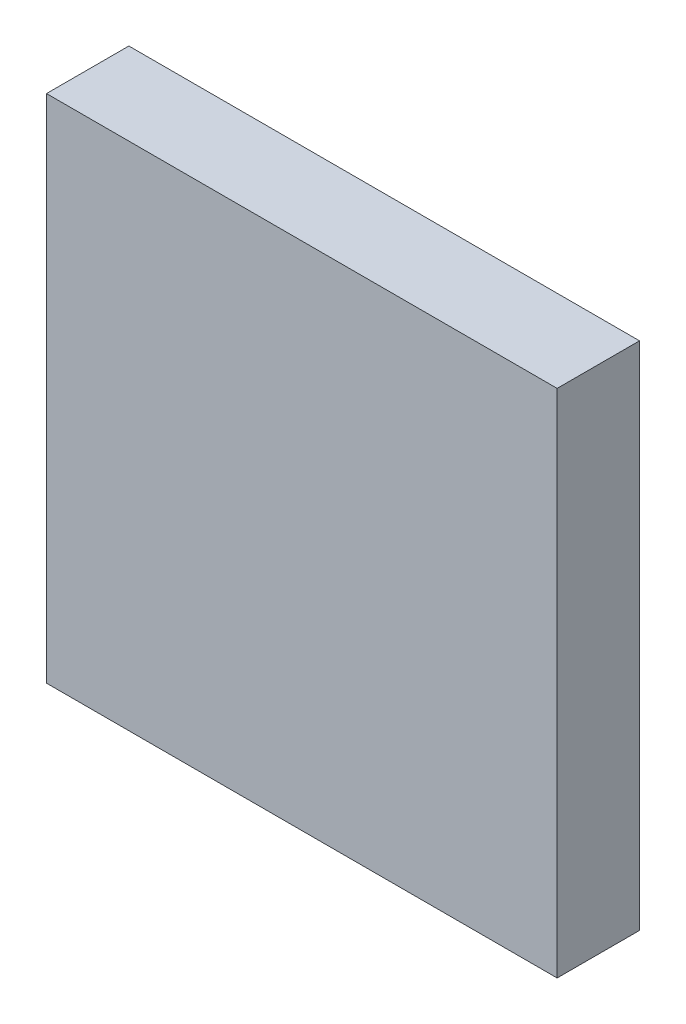
SolidWorks part; units mm, degrees
ref_plane "Спереди" through (0, 0, 0) normal (0, 0, 1) x (1, 0, 0)
ref_plane "Сверху" through (0, 0, 0) normal (0, 1, 0) x (1, 0, 0)
ref_plane "Справа" through (0, 0, 0) normal (1, 0, 0) x (0, 0, -1)
sketch "Эскиз5" plane through (0, 0, 0) normal (0, 0, 1) x (1, 0, 0)
  line L1 (-31, -31) -> (31, -31)
  line L2 (-31, -31) -> (-31, 31)
  line L3 (-31, 31) -> (31, 31)
  line L4 (31, -31) -> (31, 31)
  line L5 (-31, -31) -> (31, 31) construction
  line L6 (-31, 31) -> (31, -31) construction
  point P0 (0, 0)
extrude "Бобышка-Вытянуть2" add sketch "Эскиз5" along normal blind 10 contours L2 L3 L4 L1
sketch "Эскиз13" plane through (0, 0, 10) normal (0, 0, 1) x (1, 0, 0)
  line L1 (8.5, 3.8388) -> (8.5, -2.9703)
  line L2 (-8.5, -2.9278) -> (-8.5, 3.8388)
  spline S0 degree 3 poles (3.7602, -6.2881) (4.1456, -5.7125) (4.7609, -5.3316) (5.448, -5.2431) knots 0 0 0 0 0.333333 0.333333 0.333333 0.333333
  spline S1 degree 3 poles (5.448, -5.2431) (6.135, -5.1547) (6.8268, -5.3675) (7.3454, -5.8267) knots 0.333333 0.333333 0.333333 0.333333 1 1 1 1
  spline S2 degree 3 poles (8.2703, 4.2595) (8.4134, 4.1675) (8.5, 4.009) (8.5, 3.8388) knots 0 0 0 0 1 1 1 1
  spline S3 degree 3 poles (-8.2703, 4.2595) (-3.2319, 7.4966) (3.2319, 7.4966) (8.2703, 4.2595) knots 0 0 0 0 1 1 1 1
  spline S4 degree 3 poles (-8.5, 3.8388) (-8.5, 4.009) (-8.4134, 4.1675) (-8.2703, 4.2595) knots 0 0 0 0 1 1 1 1
  spline S5 degree 3 poles (8.9672, -4.0581) (8.6689, -3.7749) (8.5, -3.3816) (8.5, -2.9703) knots 0 0 0 0 1 1 1 1
  spline S6 degree 3 poles (8.9672, -4.0581) (9.4419, -4.5088) (9.4678, -5.2568) (9.0253, -5.7393) knots 0 0 0 0 0.333333 0.333333 0.333333 0.333333
  spline S7 degree 3 poles (9.0253, -5.7393) (8.5829, -6.2218) (7.8355, -6.2607) (7.3454, -5.8267) knots 0.333333 0.333333 0.333333 0.333333 1 1 1 1
  spline S8 degree 3 poles (-8.5, -2.9278) (-8.5, -3.3579) (-8.6732, -3.77) (-8.9805, -4.0709) knots 0 0 0 0 1 1 1 1
  spline S9 degree 3 poles (-7.6987, -6.0438) (-6.4648, -5.5547) (-5.0779, -5.6352) (-3.9089, -6.2639) knots 0 0 0 0 1 1 1 1
  spline S10 degree 3 poles (-7.6987, -6.0438) (-8.2299, -6.2544) (-8.8358, -6.0612) (-9.1472, -5.5821) knots 0 0 0 0 0.333333 0.333333 0.333333 0.333333
  spline S11 degree 3 poles (-9.1472, -5.5821) (-9.4585, -5.1029) (-9.3888, -4.4707) (-8.9805, -4.0709) knots 0.333333 0.333333 0.333333 0.333333 1 1 1 1
  spline S12 degree 3 poles (-3.1792, -6.3186) (-1.2825, -5.6394) (0.8063, -5.741) (2.6281, -6.6012) knots 0 0 0 0 1 1 1 1
  spline S13 degree 3 poles (3.7602, -6.2881) (3.5123, -6.6582) (3.0309, -6.7914) (2.6281, -6.6012) knots 0 0 0 0 1 1 1 1
  spline S14 degree 3 poles (-3.1792, -6.3186) (-3.4192, -6.4045) (-3.6844, -6.3847) (-3.9089, -6.2639) knots 0 0 0 0 1 1 1 1
sketch "остров" plane through (0, 0, 10) normal (0, 0, 1) x (1, 0, 0)
  spline S40 degree 3 poles (-5.7898, -5.6368) (-5.8728, -5.6949) (-5.9715, -5.7264) (-6.0728, -5.7271) knots 0 0 0 0 1 1 1 1
  spline S41 degree 3 poles (5.4083, -5.2485) (5.2964, -5.2648) (5.1822, -5.2427) (5.0845, -5.1857) knots 0 0 0 0 1 1 1 1
  spline S42 degree 3 poles (3.7602, -6.288) (4.1382, -5.7235) (4.7372, -5.3463) (5.4083, -5.2484) knots 0 0 0 0 0.3269 0.3269 0.3269 0.3269
  spline S47 degree 3 poles (-5.7898, -5.6368) (-2.563, -3.3793) (1.6818, -3.2032) (5.0845, -5.1857) knots 0 0 0 0 1 1 1 1
  spline S52 degree 3 poles (-6.0728, -5.7271) (-5.3265, -5.7218) (-4.5816, -5.902) (-3.9089, -6.2638) knots 0.424548 0.424548 0.424548 0.424548 1 1 1 1
  spline S55 degree 3 poles (-3.1792, -6.3185) (-1.2825, -5.6393) (0.8063, -5.7409) (2.6281, -6.6011) knots 0 0 0 0 1 1 1 1
  spline S56 degree 3 poles (3.7602, -6.288) (3.5123, -6.6581) (3.0309, -6.7913) (2.6281, -6.6011) knots 0 0 0 0 1 1 1 1
  spline S57 degree 3 poles (-3.1792, -6.3185) (-3.4192, -6.4044) (-3.6844, -6.3846) (-3.9089, -6.2638) knots 0 0 0 0 1 1 1 1
sketch "карман под съем моста" plane through (0, 0, 10) normal (0, 0, 1) x (1, 0, 0)
  line L0 (-13.7619, 0) -> (13.4181, 0) construction
  line L1 (-13.7619, 1) -> (13.4181, 1)
  line L2 (-13.7619, -1) -> (13.4181, -1)
  arc A0 (-13.7619, 1) -> (-13.7619, -1) centre (-13.7619, 0) ccw
  arc A1 (13.4181, -1) -> (13.4181, 1) centre (13.4181, 0) ccw
  point P3 (-0.1719, 0)
sketch "уголки" plane through (0, 0, 10) normal (0, 0, 1) x (1, 0, 0)
  spline S0 degree 2 poles (8.5, -2.0317) (8.5, -2.5998) (8.5, -2.9703) knots 0 0 0 1 1 1
  spline S1 degree 3 poles (5.4691, 5.3435) (5.4628, 5.5492) (5.3311, 5.73) (5.1372, 5.7991) knots 0 0 0 0 1 1 1 1
  spline S2 degree 3 poles (8.3317, 4.2129) (8.1698, 4.2866) (7.9808, 4.2686) (7.8357, 4.1657) knots 0 0 0 0 1 1 1 1
  spline S3 degree 3 poles (8.3317, 4.2129) (8.3126, 4.2298) (8.2921, 4.2455) (8.2703, 4.2595) knots 0 0 0 0 1 1 1 1
  spline S4 degree 3 poles (8.0243, -2.5311) (8.2907, -2.5182) (8.5, -2.2984) (8.5, -2.0317) knots 0 0 0 0 1 1 1 1
  spline S5 degree 3 poles (8.0243, -2.5311) (6.7965, -2.5908) (5.8123, -3.5687) (5.7445, -4.7961) knots 0 0 0 0 1 1 1 1
  spline S6 degree 3 poles (5.3331, -5.2608) (5.5614, -5.2201) (5.7318, -5.0277) (5.7445, -4.7961) knots 0 0 0 0 1 1 1 1
  spline S7 degree 3 poles (-6.4277, -5.7438) (-6.8591, -5.781) (-7.2875, -5.8808) (-7.6987, -6.0438) knots 0 0 0 0 1 1 1 1
  spline S8 degree 3 poles (-6.962, -5.1523) (-6.9912, -5.3061) (-6.9468, -5.4647) (-6.8418, -5.5808) knots 0 0 0 0 0.333333 0.333333 0.333333 0.333333
  spline S9 degree 3 poles (-6.8418, -5.5808) (-6.7369, -5.697) (-6.5837, -5.7573) (-6.4277, -5.7438) knots 0.333333 0.333333 0.333333 0.333333 1 1 1 1
  spline S10 degree 3 poles (-6.962, -5.1523) (-6.898, -4.8155) (-6.9811, -4.4674) (-7.1904, -4.1958) knots 0 0 0 0 0.333333 0.333333 0.333333 0.333333
  spline S11 degree 3 poles (-7.1904, -4.1958) (-7.3997, -3.9242) (-7.7151, -3.7551) (-8.0571, -3.7312) knots 0.333333 0.333333 0.333333 0.333333 1 1 1 1
  spline S12 degree 3 poles (-8.5169, -3.1599) (-8.5371, -3.2976) (-8.499, -3.4375) (-8.4117, -3.5459) knots 0 0 0 0 0.333333 0.333333 0.333333 0.333333
  spline S13 degree 3 poles (-8.4117, -3.5459) (-8.3245, -3.6543) (-8.196, -3.7215) (-8.0571, -3.7312) knots 0.333333 0.333333 0.333333 0.333333 1 1 1 1
  spline S14 degree 3 poles (-8.9805, -4.0709) (-8.729, -3.8247) (-8.5673, -3.504) (-8.5169, -3.1599) knots 0 0 0 0 1 1 1 1
  spline S15 degree 3 poles (-8.2703, 4.2595) (-8.2921, 4.2455) (-8.3126, 4.2298) (-8.3317, 4.2129) knots 0 0 0 0 1 1 1 1
  spline S16 degree 3 poles (-7.8357, 4.1657) (-7.9808, 4.2686) (-8.1698, 4.2866) (-8.3317, 4.2129) knots 0 0 0 0 1 1 1 1
  spline S17 degree 3 poles (-7.8357, 4.1657) (-7.3848, 3.8462) (-6.7948, 3.8005) (-6.3001, 4.0467) knots 0 0 0 0 0.333333 0.333333 0.333333 0.333333
  spline S18 degree 3 poles (-6.3001, 4.0467) (-5.8054, 4.2929) (-5.4861, 4.7912) (-5.4691, 5.3435) knots 0.333333 0.333333 0.333333 0.333333 1 1 1 1
  spline S19 degree 3 poles (-5.1372, 5.7991) (-5.3311, 5.73) (-5.4628, 5.5492) (-5.4691, 5.3435) knots 0 0 0 0 1 1 1 1
  spline S20 degree 3 poles (8.2703, 4.2595) (7.2743, 4.8994) (6.2227, 5.4129) (5.1372, 5.7991) knots 0 0 0 0 1 1 1 1
  spline S21 degree 3 poles (-5.1372, 5.7991) (-6.2227, 5.4129) (-7.2744, 4.8994) (-8.2703, 4.2595) knots 0 0 0 0 1 1 1 1
  spline S22 degree 3 poles (7.3454, -5.8267) (6.8268, -5.3675) (6.135, -5.1547) (5.448, -5.2431) knots 0 0 0 0 0.333333 0.333333 0.333333 0.333333
  spline S23 degree 3 poles (5.448, -5.2431) (5.4095, -5.2481) (5.3711, -5.254) (5.3331, -5.2608) knots 0.333333 0.333333 0.333333 0.333333 1 1 1 1
  spline S24 degree 3 poles (5.4691, 5.3435) (5.4861, 4.7912) (5.8054, 4.2929) (6.3001, 4.0467) knots 0 0 0 0 0.333333 0.333333 0.333333 0.333333
  spline S25 degree 3 poles (6.3001, 4.0467) (6.7948, 3.8005) (7.3848, 3.8462) (7.8357, 4.1657) knots 0.333333 0.333333 0.333333 0.333333 1 1 1 1
  spline S26 degree 3 poles (8.5, -2.9703) (8.5, -3.3816) (8.6689, -3.7749) (8.9672, -4.0581) knots 0 0 0 0 1 1 1 1
  spline S27 degree 3 poles (-8.9805, -4.0709) (-9.3888, -4.4707) (-9.4585, -5.1029) (-9.1472, -5.5821) knots 0 0 0 0 0.333333 0.333333 0.333333 0.333333
  spline S28 degree 3 poles (-9.1472, -5.5821) (-8.8358, -6.0612) (-8.2299, -6.2544) (-7.6987, -6.0438) knots 0.333333 0.333333 0.333333 0.333333 1 1 1 1
  spline S29 degree 3 poles (7.3454, -5.8267) (7.8355, -6.2607) (8.5829, -6.2218) (9.0253, -5.7393) knots 0 0 0 0 0.333333 0.333333 0.333333 0.333333
  spline S30 degree 3 poles (9.0253, -5.7393) (9.4678, -5.2568) (9.4419, -4.5088) (8.9672, -4.0581) knots 0.333333 0.333333 0.333333 0.333333 1 1 1 1
sketch "перлаж задник" plane through (0, 0, 10) normal (0, 0, 1) x (1, 0, 0)
  circle A0 centre (-4.6511, 5.6454) radius 1
  circle A1 centre (-3.4824, 5.7785) radius 1
  circle A2 centre (-2.3098, 5.8733) radius 1
  circle A3 centre (-1.1349, 5.9297) radius 1
  circle A4 centre (0.0413, 5.9476) radius 1
  circle A5 centre (1.2175, 5.927) radius 1
  circle A6 centre (2.3923, 5.8679) radius 1
  circle A7 centre (3.5646, 5.7704) radius 1
  circle A8 centre (4.7331, 5.6346) radius 1
  circle A9 centre (-5.0179, 4.5886) radius 1
  circle A10 centre (-3.7554, 4.7417) radius 1
  circle A11 centre (-2.4883, 4.8507) radius 1
  circle A12 centre (-1.2181, 4.9154) radius 1
  circle A13 centre (0.0535, 4.9357) radius 1
  circle A14 centre (1.3251, 4.9116) radius 1
  circle A15 centre (2.595, 4.8432) radius 1
  circle A16 centre (3.8618, 4.7305) radius 1
  circle A17 centre (5.1239, 4.5737) radius 1
  circle A18 centre (-8.123, 3.2151) radius 1
  circle A19 centre (-7.0541, 3.4447) radius 1
  circle A20 centre (-5.9787, 3.6418) radius 1
  circle A21 centre (-4.8979, 3.8064) radius 1
  circle A22 centre (-3.8126, 3.9381) radius 1
  circle A23 centre (-2.7238, 4.037) radius 1
  circle A24 centre (-1.6325, 4.1029) radius 1
  circle A25 centre (-0.5398, 4.1358) radius 1
  circle A26 centre (0.5535, 4.1356) radius 1
  circle A27 centre (1.6463, 4.1023) radius 1
  circle A28 centre (2.7375, 4.036) radius 1
  circle A29 centre (3.8263, 3.9367) radius 1
  circle A30 centre (4.9116, 3.8045) radius 1
  circle A31 centre (5.9923, 3.6396) radius 1
  circle A32 centre (7.0676, 3.442) radius 1
  circle A33 centre (8.1364, 3.212) radius 1
  circle A34 centre (-8.1008, 2.0704) radius 1
  circle A35 centre (-6.96, 2.3145) radius 1
  circle A36 centre (-5.8119, 2.5215) radius 1
  circle A37 centre (-4.6577, 2.6912) radius 1
  circle A38 centre (-3.4986, 2.8234) radius 1
  circle A39 centre (-2.3358, 2.9179) radius 1
  circle A40 centre (-1.1706, 2.9748) radius 1
  circle A41 centre (-0.0041, 2.9938) radius 1
  circle A42 centre (1.1624, 2.975) radius 1
  circle A43 centre (2.3276, 2.9185) radius 1
  circle A44 centre (3.4904, 2.8242) radius 1
  circle A45 centre (4.6496, 2.6922) radius 1
  circle A46 centre (5.8038, 2.5228) radius 1
  circle A47 centre (6.952, 2.3161) radius 1
  circle A48 centre (8.0929, 2.0722) radius 1
  circle A49 centre (-8.0193, 0.9076) radius 1
  circle A50 centre (-6.8839, 1.1491) radius 1
  circle A51 centre (-5.7411, 1.3538) radius 1
  circle A52 centre (-4.5924, 1.5213) radius 1
  circle A53 centre (-3.4388, 1.6514) radius 1
  circle A54 centre (-2.2816, 1.7441) radius 1
  circle A55 centre (-1.1221, 1.7993) radius 1
  circle A56 centre (0.0387, 1.8169) radius 1
  circle A57 centre (1.1994, 1.7968) radius 1
  circle A58 centre (2.3589, 1.7391) radius 1
  circle A59 centre (3.5158, 1.6439) radius 1
  circle A60 centre (4.6691, 1.5112) radius 1
  circle A61 centre (5.8175, 1.3413) radius 1
  circle A62 centre (6.9598, 1.1342) radius 1
  circle A63 centre (8.0947, 0.8902) radius 1
  circle A64 centre (-7.9633, -0.2579) radius 1
  circle A65 centre (-6.8332, -0.0181) radius 1
  circle A66 centre (-5.6959, 0.185) radius 1
  circle A67 centre (-4.5527, 0.3511) radius 1
  circle A68 centre (-3.4046, 0.4801) radius 1
  circle A69 centre (-2.253, 0.5718) radius 1
  circle A70 centre (-1.099, 0.6261) radius 1
  circle A71 centre (0.0561, 0.643) radius 1
  circle A72 centre (1.2112, 0.6225) radius 1
  circle A73 centre (2.365, 0.5645) radius 1
  circle A74 centre (3.5163, 0.4692) radius 1
  circle A75 centre (4.6639, 0.3366) radius 1
  circle A76 centre (5.8066, 0.1669) radius 1
  circle A77 centre (6.9433, -0.0397) radius 1
  circle A78 centre (8.0726, -0.2831) radius 1
  circle A79 centre (-7.9918, -1.4333) radius 1
  circle A80 centre (-6.8673, -1.1924) radius 1
  circle A81 centre (-5.7357, -0.9882) radius 1
  circle A82 centre (-4.598, -0.8207) radius 1
  circle A83 centre (-3.4555, -0.6901) radius 1
  circle A84 centre (-2.3094, -0.5967) radius 1
  circle A85 centre (-1.1609, -0.5405) radius 1
  circle A86 centre (-0.0111, -0.5215) radius 1
  circle A87 centre (1.1387, -0.5397) radius 1
  circle A88 centre (2.2873, -0.5953) radius 1
  circle A89 centre (3.4334, -0.688) radius 1
  circle A90 centre (4.576, -0.8178) radius 1
  circle A91 centre (5.7138, -0.9846) radius 1
  circle A92 centre (6.8455, -1.1881) radius 1
  circle A93 centre (7.9701, -1.4283) radius 1
  circle A94 centre (-8.0131, -2.6484) radius 1
  circle A95 centre (-6.9172, -2.4111) radius 1
  circle A96 centre (-5.8144, -2.2087) radius 1
  circle A97 centre (-4.7056, -2.0415) radius 1
  circle A98 centre (-3.5921, -1.9096) radius 1
  circle A99 centre (-2.4749, -1.8131) radius 1
  circle A100 centre (-1.3553, -1.7522) radius 1
  circle A101 centre (-0.2343, -1.727) radius 1
  circle A102 centre (0.887, -1.7374) radius 1
  circle A103 centre (2.0074, -1.7834) radius 1
  circle A104 centre (3.1257, -1.865) radius 1
  circle A105 centre (4.2409, -1.9821) radius 1
  circle A106 centre (5.3517, -2.1346) radius 1
  circle A107 centre (6.4572, -2.3223) radius 1
  circle A108 centre (7.5562, -2.545) radius 1
  circle A109 centre (-7.0918, -3.6392) radius 1
  circle A110 centre (-5.9238, -3.4052) radius 1
  circle A111 centre (-4.7481, -3.2133) radius 1
  circle A112 centre (-3.5663, -3.0638) radius 1
  circle A113 centre (-2.3798, -2.9568) radius 1
  circle A114 centre (-1.1903, -2.8926) radius 1
  circle A115 centre (0.0008, -2.8713) radius 1
  circle A116 centre (1.1919, -2.8927) radius 1
  circle A117 centre (2.3814, -2.957) radius 1
  circle A118 centre (3.5678, -3.0639) radius 1
  circle A119 centre (4.7497, -3.2135) radius 1
  circle A120 centre (5.9253, -3.4055) radius 1
  circle A121 centre (-6.2553, -4.6679) radius 1
  circle A122 centre (-5.1231, -4.4693) radius 1
  circle A123 centre (-3.9847, -4.3103) radius 1
  circle A124 centre (-2.8414, -4.1912) radius 1
  circle A125 centre (-1.6947, -4.112) radius 1
  circle A126 centre (-0.5458, -4.0729) radius 1
  circle A127 centre (0.6036, -4.0739) radius 1
  circle A128 centre (1.7524, -4.115) radius 1
  circle A129 centre (2.899, -4.1962) radius 1
  circle A130 centre (4.042, -4.3173) radius 1
  circle A131 centre (5.1802, -4.4783) radius 1
  circle A132 centre (-5.6707, -5.6462) radius 1
  circle A133 centre (-4.4381, -5.46) radius 1
  circle A134 centre (-3.1996, -5.3193) radius 1
  circle A135 centre (-1.9567, -5.2243) radius 1
  circle A136 centre (-0.7112, -5.1751) radius 1
  circle A137 centre (0.5353, -5.1719) radius 1
  circle A138 centre (1.7811, -5.2145) radius 1
  circle A139 centre (3.0245, -5.3031) radius 1
  circle A140 centre (4.2637, -5.4374) radius 1
  circle A141 centre (5.4972, -5.6172) radius 1
  circle A142 centre (-4.869, -6.5621) radius 1
  circle A143 centre (-3.7069, -6.4218) radius 1
  circle A144 centre (-2.5409, -6.3195) radius 1
  circle A145 centre (-1.3721, -6.2555) radius 1
  circle A146 centre (-0.2018, -6.2298) radius 1
  circle A147 centre (0.9687, -6.2423) radius 1
  circle A148 centre (2.1381, -6.2931) radius 1
  circle A149 centre (3.3053, -6.3822) radius 1
  circle A150 centre (4.4689, -6.5094) radius 1
  point P24 (0, -30)
  point P43 (0, -31.5)
  point P76 (0, -32)
  point P107 (0, -33)
  point P138 (0, -34)
  point P169 (0, -35)
  point P200 (0, -36)
  point P231 (0, -37)
  point P256 (0, -36)
  point P279 (0, -37)
  point P300 (0, -39)
  point P319 (0, -42)
  dimension "D1" = 9
  dimension "D2" = 9
  dimension "D3" = 16
  dimension "D4" = 15
  dimension "D5" = 15
  dimension "D6" = 15
  dimension "D7" = 15
  dimension "D8" = 15
  dimension "D9" = 12
  dimension "D10" = 11
  dimension "D11" = 10
  dimension "D12" = 9
sketch "подточка" plane through (0, 0, 10) normal (0, 0, 1) x (1, 0, 0)
  circle A0 centre (-8.7716, 9.2306) radius 1
  circle A1 centre (-5.299, 10.4616) radius 1
  circle A2 centre (-1.6654, 11.0709) radius 1
  circle A3 centre (2.0189, 11.04) radius 1
  circle A4 centre (5.6417, 10.3697) radius 1
  circle A5 centre (9.0932, 9.0806) radius 1
  point P15 (0, -10)
  dimension "D1" = 6
sketch "Перлаж сетка"
  point P35 (0, -9)
  point P68 (0, -10)
  dimension "D1" = 11
sketch_block_instance "Блок4-18"
sketch_block "Блок4"
sketch_block_instance "Блок4-19"
sketch_block_instance "Блок4-20"
sketch_block_instance "Блок4-21"
sketch_block_instance "Блок4-22"
sketch_block_instance "Блок4-23"
sketch_block_instance "Блок4-24"
sketch_block_instance "Блок4-25"
sketch_block_instance "Блок5-1"
sketch_block "Блок5"
sketch_block_instance "Блок5-2"
sketch_block_instance "Блок5-3"
sketch_block_instance "Блок5-4"
sketch_block_instance "Блок5-5"
sketch_block_instance "Блок5-6"
sketch_block_instance "Блок5-7"
sketch_block_instance "Блок5-8"
sketch_block_instance "Блок5-9"
sketch_block_instance "Блок5-10"
sketch_block_instance "Блок5-11"
